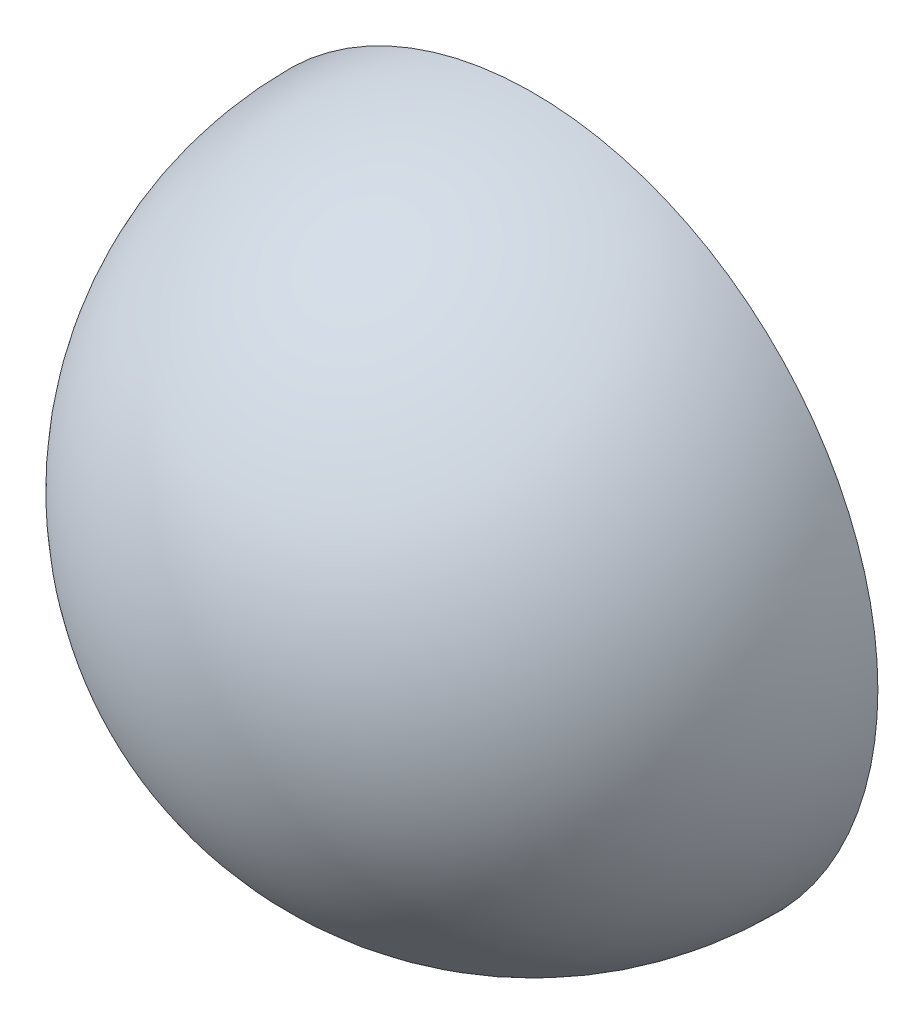
SolidWorks part; units mm, degrees
ref_plane "Front Plane" through (0, 0, 0) normal (0, 0, 1) x (1, 0, 0)
ref_plane "Top Plane" through (0, 0, 0) normal (0, 1, 0) x (1, 0, 0)
ref_plane "Right Plane" through (0, 0, 0) normal (1, 0, 0) x (0, 0, -1)
sketch "Sketch1" plane through (0, 0, 0) normal (0, 0, 1) x (1, 0, 0)
  line L0 (-9.6972, 0) -> (9.6972, 0)
  arc A0 (9.6972, 0) -> (-9.6972, 0) centre (0, 0) ccw
revolve "Revolve1" add sketch "Sketch1" angle 180 about L0
